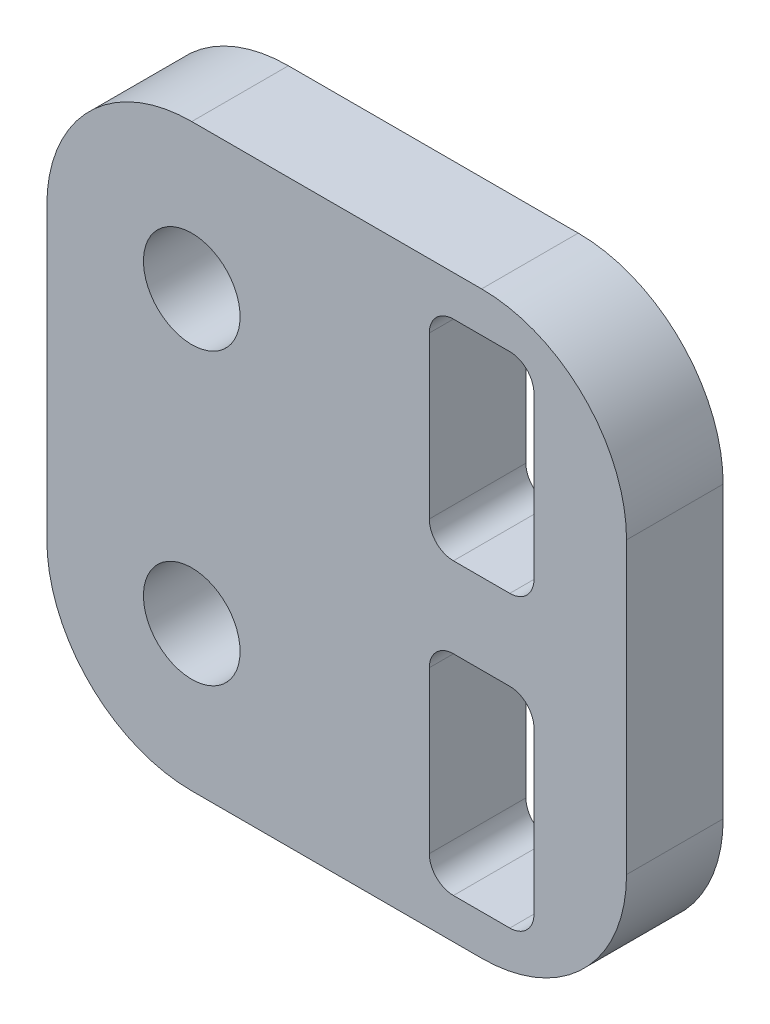
SolidWorks part; units mm, degrees
ref_plane "Alzado" through (0, 0, 0) normal (0, 0, 1) x (1, 0, 0)
ref_plane "Planta" through (0, 0, 0) normal (0, 1, 0) x (1, 0, 0)
ref_plane "Vista lateral" through (0, 0, 0) normal (1, 0, 0) x (0, 0, -1)
sketch "Model" plane through (0, 0, 0) normal (0, 0, 1) x (1, 0, 0)
  line L0 (195.3359, 161.3332) -> (204.3359, 161.3332)
  line L1 (208.8359, 165.8332) -> (208.8359, 174.8332)
  line L2 (204.3359, 179.3332) -> (195.3359, 179.3332)
  line L3 (190.8359, 174.8332) -> (190.8359, 165.8332)
  line L4 (202.7109, 172.3332) -> (202.7109, 177.3332)
  line L5 (203.4609, 178.0832) -> (205.2109, 178.0832)
  line L6 (205.9609, 177.3332) -> (205.9609, 172.3332)
  line L7 (205.2109, 171.5832) -> (203.4609, 171.5832)
  line L8 (205.9609, 168.3332) -> (205.9609, 163.3332)
  line L9 (205.2109, 162.5832) -> (203.4609, 162.5832)
  line L10 (202.7109, 163.3332) -> (202.7109, 168.3332)
  line L11 (203.4609, 169.0832) -> (205.2109, 169.0832)
  circle A0 centre (195.3359, 174.8332) radius 1.5
  circle A1 centre (195.3359, 165.8332) radius 1.5
  arc A2 (204.3359, 161.3332) -> (208.8359, 165.8332) centre (204.3359, 165.8332) ccw
  arc A3 (208.8359, 174.8332) -> (204.3359, 179.3332) centre (204.3359, 174.8332) ccw
  arc A4 (195.3359, 179.3332) -> (190.8359, 174.8332) centre (195.3359, 174.8332) ccw
  arc A5 (190.8359, 165.8332) -> (195.3359, 161.3332) centre (195.3359, 165.8332) ccw
  arc A6 (203.4609, 178.0832) -> (202.7109, 177.3332) centre (203.4609, 177.3332) ccw
  arc A7 (205.9609, 177.3332) -> (205.2109, 178.0832) centre (205.2109, 177.3332) ccw
  arc A8 (205.2109, 171.5832) -> (205.9609, 172.3332) centre (205.2109, 172.3332) ccw
  arc A9 (202.7109, 172.3332) -> (203.4609, 171.5832) centre (203.4609, 172.3332) ccw
  arc A10 (205.2109, 162.5832) -> (205.9609, 163.3332) centre (205.2109, 163.3332) ccw
  arc A11 (202.7109, 163.3332) -> (203.4609, 162.5832) centre (203.4609, 163.3332) ccw
  arc A12 (203.4609, 169.0832) -> (202.7109, 168.3332) centre (203.4609, 168.3332) ccw
  arc A13 (205.9609, 168.3332) -> (205.2109, 169.0832) centre (205.2109, 168.3332) ccw
extrude "Saliente-Extruir1" add sketch "Model" along normal blind 3
